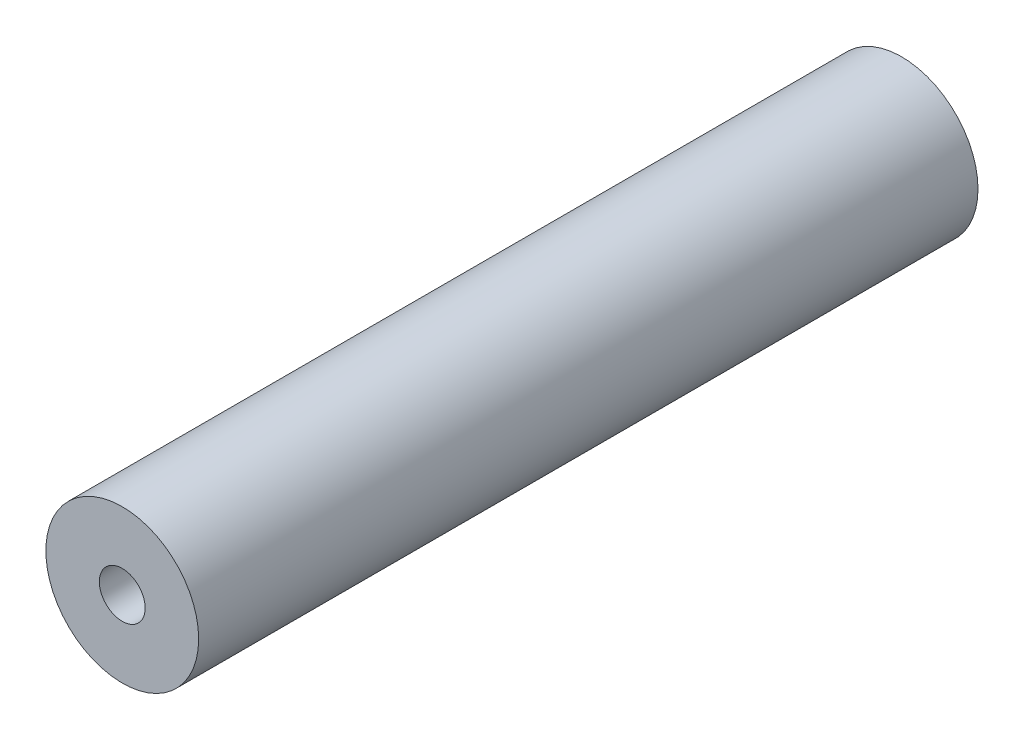
SolidWorks part; units mm, degrees
ref_plane "Front Plane" through (0, 0, 0) normal (0, 0, 1) x (1, 0, 0)
ref_plane "Top Plane" through (0, 0, 0) normal (0, 1, 0) x (1, 0, 0)
ref_plane "Right Plane" through (0, 0, 0) normal (1, 0, 0) x (0, 0, -1)
sketch "Sketch1" plane through (0, 0, 0) normal (0, 0, 1) x (1, 0, 0)
  circle A0 centre (0, 0) radius 1.5
  circle A1 centre (0, 0) radius 5
  dimension "D1" = 10
  dimension "D2" = 3
extrude "Boss-Extrude1" add sketch "Sketch1" along normal blind 51
